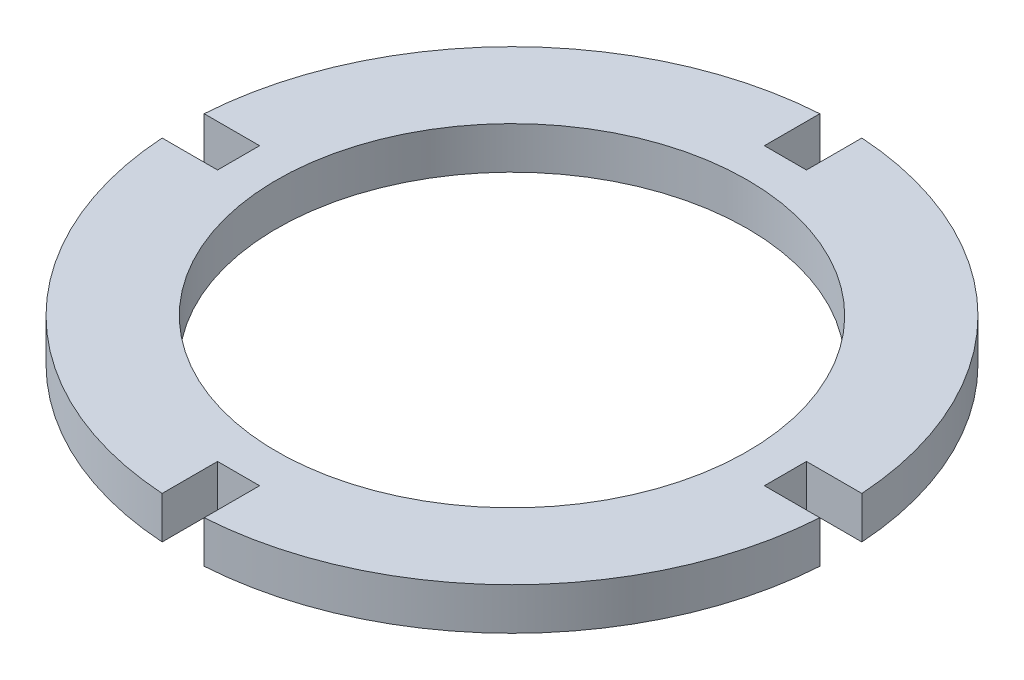
SolidWorks part; units mm, degrees
ref_plane "Přední rovina" through (0, 0, 0) normal (0, 0, 1) x (1, 0, 0)
ref_plane "Horní rovina" through (0, 0, 0) normal (0, 1, 0) x (1, 0, 0)
ref_plane "Pravá rovina" through (0, 0, 0) normal (1, 0, 0) x (0, 0, -1)
sketch "Skica4" plane through (0, 0, 0) normal (0, 1, 0) x (1, 0, 0)
  line L0 (3.6977, 23.2073) -> (-4.1764, -26.2115) construction
  circle A0 centre (0, 0) radius 23.5
  circle A1 centre (0, 0) radius 16.78
  dimension "D1" = 47
  dimension "D2" = 33.56
extrude "Přidat vysunutím1" add sketch "Skica4" along normal blind 3 contours A0
sketch "Skica6" plane through (0, 0, 0) normal (0, -1, 0) x (1, 0, 0)
  circle A0 centre (0, 0) radius 16.78
  dimension "D1" = 33.56
extrude "Odebrat vysunutím2" cut sketch "Skica6" against normal blind 3
sketch "Skica7" plane through (0, 3, 0) normal (0, 1, 0) x (1, 0, 0)
  line L0 (-26.0262, 0) -> (28.1534, 0) construction
  line L1 (0, -25.5181) -> (0, 30.2607) construction
  line L2 (1.5, -19.5) -> (-1.5, -19.5)
  line L3 (19.5, 1.5) -> (25.8822, 1.5)
  line L4 (19.5, 1.5) -> (19.5, -1.5)
  line L5 (19.5, -1.5) -> (25.8822, -1.5)
  line L6 (25.8822, 1.5) -> (25.8822, -1.5)
  line L7 (19.5, 1.5) -> (25.8822, -1.5) construction
  line L8 (19.5, -1.5) -> (25.8822, 1.5) construction
  line L9 (1.5, -19.5) -> (1.5, -25.8822)
  line L10 (1.5, -25.8822) -> (-1.5, -25.8822)
  line L11 (-1.5, -19.5) -> (-1.5, -25.8822)
  line L12 (-19.5, -1.5) -> (-19.5, 1.5)
  line L13 (-19.5, -1.5) -> (-25.8822, -1.5)
  line L14 (-25.8822, -1.5) -> (-25.8822, 1.5)
  line L15 (-19.5, 1.5) -> (-25.8822, 1.5)
  line L16 (-1.5, 19.5) -> (1.5, 19.5)
  line L17 (-1.5, 19.5) -> (-1.5, 25.8822)
  line L18 (-1.5, 25.8822) -> (1.5, 25.8822)
  line L19 (1.5, 19.5) -> (1.5, 25.8822)
  point P6 (22.6911, 0)
  point P26 (0, 0)
  dimension "D1" = 19.5
  dimension "D2" = 3
  dimension "D3" = 4
extrude "Odebrat vysunutím3" cut sketch "Skica7" against normal blind 3
